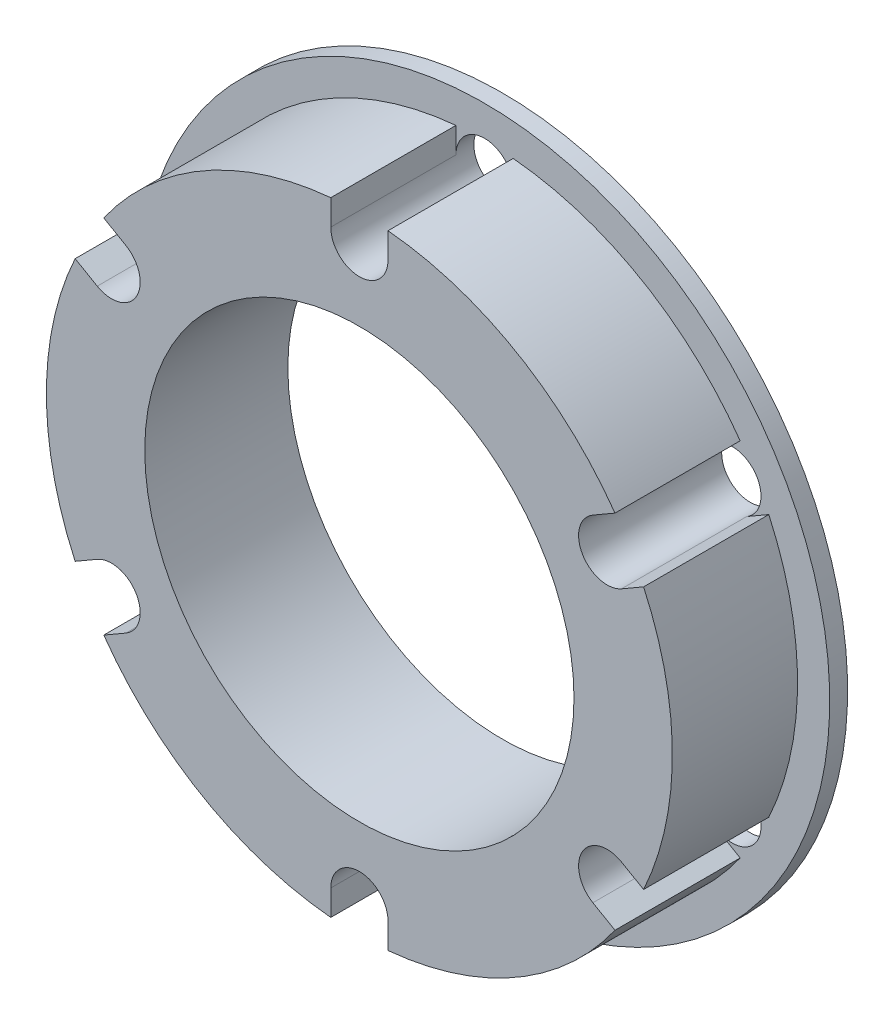
SolidWorks part; units mm, degrees
material "ABS"
ref_plane "Front" through (0, 0, 0) normal (0, 0, 1) x (1, 0, 0)
ref_plane "Top" through (0, 0, 0) normal (0, 1, 0) x (1, 0, 0)
ref_plane "Right" through (0, 0, 0) normal (1, 0, 0) x (0, 0, -1)
sketch "Croquis1" plane through (0, 0, 0) normal (0, 1, 0) x (1, 0, 0)
  line L0 (-12, 4.5) -> (-19.3, 4.5)
  line L1 (-19.3, 4.5) -> (-19.3, 3.5)
  line L2 (-19.3, 3.5) -> (-17.5, 3.5)
  line L3 (-17.5, 3.5) -> (-17.5, -3.5)
  line L4 (-17.5, -3.5) -> (-12, -3.5)
  line L5 (-12, -3.5) -> (-12, 4.5)
  line L6 (0, -55) -> (0, 55) construction
  line L7 (-55, 0) -> (55, 0) construction
  line L8 (0, 14.9098) -> (0, -20.3901) construction
  point P8 (-17.5, 0)
  dimension "D1" = 12
  dimension "D2" = 7
  dimension "D3" = 1
  dimension "D4" = 17.5
  dimension "D5" = 19.3
revolve "Revolución1" add sketch "Croquis1" angle 360 about L8
sketch "Croquis2" plane through (0, 0, 3.5) normal (0, 0, 1) x (1, 0, 0)
  line L0 (0, -4.4) -> (0, 4.4) construction
  line L1 (1.6, 16) -> (1.6, 17.4267)
  line L2 (-1.6, 16) -> (-1.6, 17.4267)
  line L3 (4.4, 0) -> (-4.4, 0) construction
  line L4 (14.6564, 6.6144) -> (15.892, 7.3277)
  line L5 (13.0564, 9.3856) -> (14.292, 10.099)
  line L6 (13.0564, -9.3856) -> (14.292, -10.099)
  line L7 (14.6564, -6.6144) -> (15.892, -7.3277)
  line L8 (-1.6, -16) -> (-1.6, -17.4267)
  line L9 (1.6, -16) -> (1.6, -17.4267)
  line L10 (-14.6564, -6.6144) -> (-15.892, -7.3277)
  line L11 (-13.0564, -9.3856) -> (-14.292, -10.099)
  line L12 (-13.0564, 9.3856) -> (-14.292, 10.099)
  line L13 (-14.6564, 6.6144) -> (-15.892, 7.3277)
  circle A1 centre (0, 0) radius 17.5 construction
  circle A2 centre (0, 0) radius 17.5 construction
  arc A3 (1.6, 17.4267) -> (-1.6, 17.4267) centre (0, 0) ccw
  arc A4 (-1.6, 16) -> (1.6, 16) centre (0, 16) ccw
  arc A5 (15.892, 7.3277) -> (14.292, 10.099) centre (0, 0) ccw
  arc A6 (13.0564, 9.3856) -> (14.6564, 6.6144) centre (13.8564, 8) ccw
  arc A7 (14.292, -10.099) -> (15.892, -7.3277) centre (0, 0) ccw
  arc A8 (14.6564, -6.6144) -> (13.0564, -9.3856) centre (13.8564, -8) ccw
  arc A9 (-1.6, -17.4267) -> (1.6, -17.4267) centre (0, 0) ccw
  arc A10 (1.6, -16) -> (-1.6, -16) centre (0, -16) ccw
  arc A11 (-15.892, -7.3277) -> (-14.292, -10.099) centre (0, 0) ccw
  arc A12 (-13.0564, -9.3856) -> (-14.6564, -6.6144) centre (-13.8564, -8) ccw
  arc A13 (-14.292, 10.099) -> (-15.892, 7.3277) centre (0, 0) ccw
  arc A14 (-14.6564, 6.6144) -> (-13.0564, 9.3856) centre (-13.8564, 8) ccw
  dimension "D1" = 1.6
  dimension "D2" = 16
  dimension "D3" = 6
extrude "Cortar-Extruir1" cut sketch "Croquis2" against normal up to surface (7 mm away) up to face at (-17.5, 0, -3.5)
sketch "Croquis5" plane through (0, 0, -4.5) normal (0, 0, -1) x (-1, 0, 0)
  line L0 (0, 4.4) -> (0, -4.4) construction
  line L1 (4.4, 0) -> (-4.4, 0) construction
  circle A0 centre (0, 16) radius 1.6
  circle A1 centre (13.8564, 8) radius 1.6
  circle A2 centre (13.8564, -8) radius 1.6
  circle A3 centre (0, -16) radius 1.6
  circle A4 centre (-13.8564, -8) radius 1.6
  circle A5 centre (-13.8564, 8) radius 1.6
  dimension "D1" = 3.2
  dimension "D2" = 16
  dimension "D3" = 6
extrude "Cortar-Extruir2" cut sketch "Croquis5" against normal up to next
